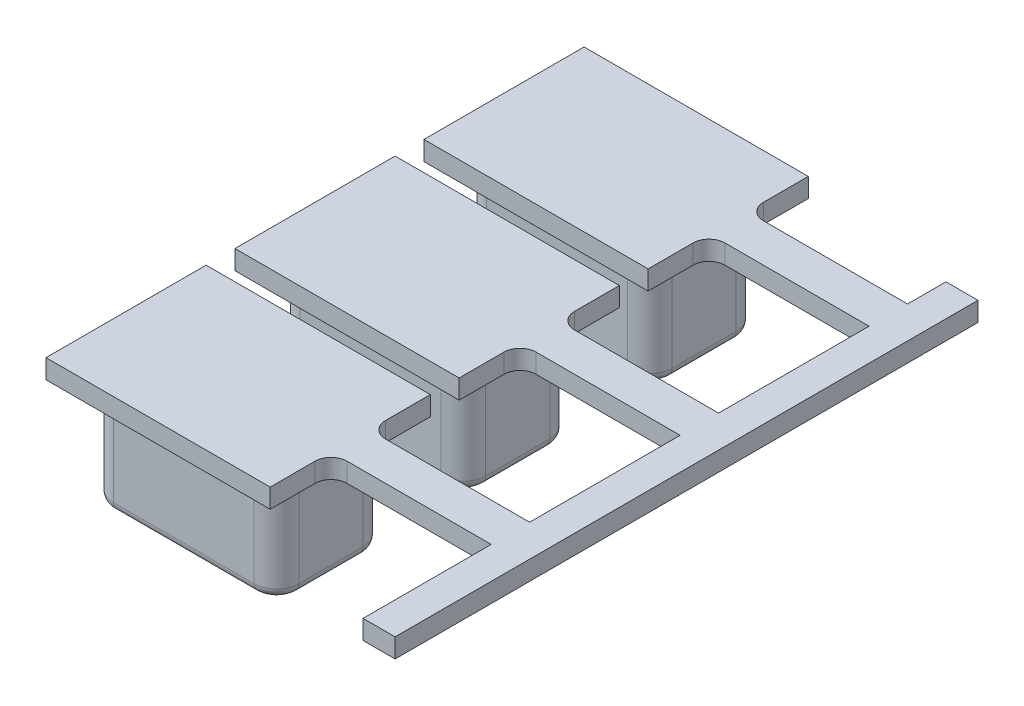
SolidWorks part; units mm, degrees
ref_plane "前视基准面" through (0, 0, 0) normal (0, 0, 1) x (1, 0, 0)
ref_plane "上视基准面" through (0, 0, 0) normal (0, 1, 0) x (1, 0, 0)
ref_plane "右视基准面" through (0, 0, 0) normal (1, 0, 0) x (0, 0, -1)
sketch "草图1" plane through (0, 0, 0) normal (0, 1, 0) x (1, 0, 0)
  line L0 (-2.2, 1.7) -> (2.2, 1.7)
  line L5 (-2.2, 7.5287) -> (2.2, 7.5287)
  line L6 (2.9, 6.8287) -> (2.9, 4.8287)
  line L7 (2.9, 1) -> (2.9, -1)
  line L8 (-2.2, -1.7) -> (2.2, -1.7)
  line L9 (-2.9, 1) -> (-2.9, -1)
  line L10 (-2.2, 4.1287) -> (2.2, 4.1287)
  line L11 (-2.9, 6.8287) -> (-2.9, 4.8287)
  line L12 (-2.2, 13.3491) -> (2.2, 13.3491)
  line L13 (2.9, 12.6491) -> (2.9, 10.6491)
  line L14 (-2.2, 9.9491) -> (2.2, 9.9491)
  line L15 (-2.9, 12.6491) -> (-2.9, 10.6491)
  arc A4 (2.2, 1.7) -> (2.9, 1) centre (2.2, 1) cw
  arc A5 (2.2, -1.7) -> (2.9, -1) centre (2.2, -1) ccw
  arc A6 (-2.9, -1) -> (-2.2, -1.7) centre (-2.2, -1) ccw
  arc A7 (-2.2, 1.7) -> (-2.9, 1) centre (-2.2, 1) ccw
  arc A8 (2.2, 7.5287) -> (2.9, 6.8287) centre (2.2, 6.8287) cw
  arc A9 (2.2, 4.1287) -> (2.9, 4.8287) centre (2.2, 4.8287) ccw
  arc A10 (-2.9, 4.8287) -> (-2.2, 4.1287) centre (-2.2, 4.8287) ccw
  arc A11 (-2.2, 7.5287) -> (-2.9, 6.8287) centre (-2.2, 6.8287) ccw
  arc A12 (2.2, 13.3491) -> (2.9, 12.6491) centre (2.2, 12.6491) cw
  arc A13 (2.2, 9.9491) -> (2.9, 10.6491) centre (2.2, 10.6491) ccw
  arc A14 (-2.9, 10.6491) -> (-2.2, 9.9491) centre (-2.2, 10.6491) ccw
  arc A15 (-2.2, 13.3491) -> (-2.9, 12.6491) centre (-2.2, 12.6491) ccw
  point P0 (0, 0)
  point P1 (-0.0497, 5.8287)
  point P15 (-0.0145, 11.6491)
  dimension "D1" = 3.4
  dimension "D2" = 5.8
extrude "凸台-拉伸1" add sketch "草图1" along normal blind 4
sketch "草图2" plane through (0, 4, 0) normal (0, 1, 0) x (1, 0, 0)
  line L1 (-3.4633, 14.2631) -> (3.5367, 14.2631)
  line L2 (-3.4633, 14.2631) -> (-3.4633, 9.2631)
  line L3 (-3.4633, 9.2631) -> (3.5367, 9.2631)
  line L4 (3.5367, 14.2631) -> (3.5367, 9.2631)
  line L5 (-3.4633, 8.3631) -> (3.5367, 8.3631)
  line L6 (-3.4633, 8.3631) -> (-3.4633, 3.3631)
  line L7 (-3.4633, 3.3631) -> (3.5367, 3.3631)
  line L8 (3.5367, 8.3631) -> (3.5367, 3.3631)
  line L9 (3.5367, 2.4631) -> (-3.4633, 2.4631)
  line L10 (3.5367, 2.4631) -> (3.5367, -2.5369)
  line L11 (3.5367, -2.5369) -> (-3.4633, -2.5369)
  line L12 (-3.4633, 2.4631) -> (-3.4633, -2.5369)
  dimension "D1" = 5
  dimension "D2" = 5
  dimension "D3" = 5
  dimension "D4" = 7
  dimension "D5" = 0.9
  dimension "D6" = 0.9
extrude "凸台-拉伸2" add sketch "草图2" against normal blind 0.6
sketch "草图3" plane through (0, 4, 0) normal (0, 1, 0) x (1, 0, 0)
  line L0 (3.5367, 9.2631) -> (3.5367, 14.2631) construction
  line L1 (3.5367, 12.3631) -> (9.5367, 12.3631)
  line L2 (3.5367, 12.3631) -> (3.5367, 11.1631)
  line L3 (3.5367, 11.1631) -> (9.5367, 11.1631)
  line L4 (9.5367, 12.3631) -> (9.5367, 11.1631)
  line L5 (3.5367, 3.3631) -> (3.5367, 8.3631) construction
  line L6 (3.5367, 6.4631) -> (9.5367, 6.4631)
  line L7 (3.5367, 6.4631) -> (3.5367, 5.2631)
  line L8 (3.5367, 5.2631) -> (9.5367, 5.2631)
  line L9 (9.5367, 6.4631) -> (9.5367, 5.2631)
  line L10 (3.5367, -2.5369) -> (3.5367, 2.4631) construction
  line L11 (3.5367, 0.5631) -> (9.5367, 0.5631)
  line L12 (3.5367, 0.5631) -> (3.5367, -0.6369)
  line L13 (3.5367, -0.6369) -> (9.5367, -0.6369)
  line L14 (9.5367, 0.5631) -> (9.5367, -0.6369)
  line L15 (-3.4633, 14.2631) -> (-3.4633, 9.2631) construction
  line L16 (-3.4633, 8.3631) -> (-3.4633, 3.3631) construction
  line L17 (-3.4633, 2.4631) -> (-3.4633, -2.5369) construction
  point P20 (-3.4633, 11.7631)
  point P21 (9.5367, 11.7631)
  point P24 (-3.4633, 5.8631)
  point P25 (9.5367, 5.8631)
  point P28 (-3.4633, -0.0369)
  point P29 (9.5367, -0.0369)
  dimension "D3" = 1.2
  dimension "D4" = 6
extrude "凸台-拉伸3" add sketch "草图3" against normal blind 0.6
sketch "草图4" plane through (0, 3.4, 0) normal (0, -1, 0) x (1, 0, 0)
  line L0 (3.5367, 0.6369) -> (9.5367, 0.6369) construction
  line L1 (9.5367, 0.6369) -> (8.5367, 0.6369)
  line L2 (9.5367, 0.6369) -> (9.5367, -12.3631)
  line L3 (9.5367, -12.3631) -> (8.5367, -12.3631)
  line L4 (8.5367, 0.6369) -> (8.5367, -12.3631)
  line L5 (9.5367, -12.3631) -> (3.5367, -12.3631) construction
  dimension "D1" = 1
extrude "凸台-拉伸4" add sketch "草图4" against normal blind 0.6
fillet "圆角1" radius 0.5 6 edges at (3.5367, 3.7, -12.3631) (3.5367, 3.7, -11.1631) (3.5367, 3.7, -5.2631) (3.5367, 3.7, -6.4631) (3.5367, 3.7, 0.6369) (3.5367, 3.7, -0.5631)
sketch "草图5" plane through (0, 0, -12.3631) normal (0, 0, -1) x (-1, 0, 0)
  line L0 (-4.0367, 4) -> (-9.5367, 4) construction
  line L1 (-9.5367, 3.4) -> (-8.5367, 3.4)
  line L2 (-9.5367, 3.4) -> (-9.5367, 4)
  line L3 (-9.5367, 4) -> (-8.5367, 4)
  line L4 (-8.5367, 3.4) -> (-8.5367, 4)
  dimension "D1" = 1
  dimension "D2" = 0.6
extrude "凸台-拉伸5" add sketch "草图5" along normal blind 1.2
fillet "圆角2" radius 0.3 24 edges at (2.695, 0, -13.1441) (2.9, 0, -11.6491) (2.695, 0, -10.1542) (0, 0, -9.9491) (-2.695, 0, -10.1542) (-2.9, 0, -11.6491) (-2.695, 0, -13.1441) (2.695, 0, -7.3237) (2.9, 0, -5.8287) (2.695, 0, -4.3337) (0, 0, -4.1287) (-2.695, 0, -4.3337) (-2.9, 0, -5.8287) (-2.695, 0, -7.3237) (2.695, 0, -1.495) (2.9, 0, 0) (2.695, 0, 1.495) (0, 0, 1.7) (-2.695, 0, 1.495) (-2.9, 0, 0) (-2.695, 0, -1.495) (0, 0, -13.3491) (0, 0, -7.5287) (0, 0, -1.7)
sketch "草图7" plane through (0, 0, 0.6369) normal (0, 0, 1) x (1, 0, 0)
  line L0 (4.0367, 4) -> (9.5367, 4) construction
  line L1 (9.5367, 3.4) -> (8.5367, 3.4)
  line L2 (9.5367, 3.4) -> (9.5367, 4)
  line L3 (9.5367, 4) -> (8.5367, 4)
  line L4 (8.5367, 3.4) -> (8.5367, 4)
extrude "凸台-拉伸6" add sketch "草图7" along normal blind 4
